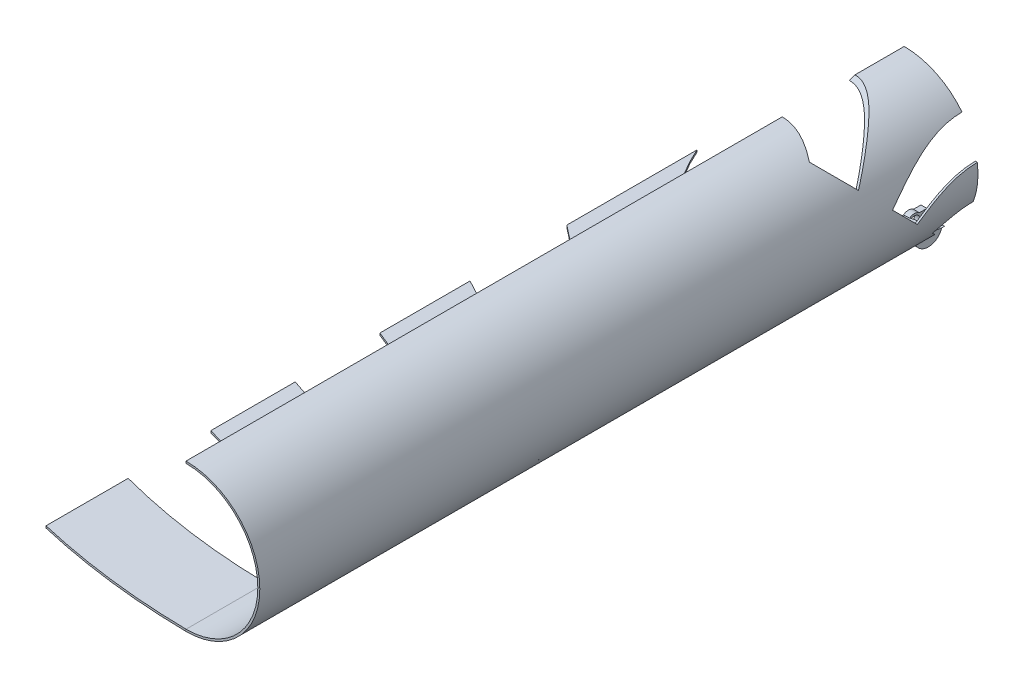
SolidWorks part; units mm, degrees
ref_plane "前视基准面" through (0, 0, 0) normal (0, 0, 1) x (1, 0, 0)
ref_plane "上视基准面" through (0, 0, 0) normal (0, 1, 0) x (1, 0, 0)
ref_plane "右视基准面" through (0, 0, 0) normal (1, 0, 0) x (0, 0, -1)
sketch "草图1" plane through (0, 0, 0) normal (0, 0, 1) x (1, 0, 0)
  circle A0 centre (0, 0) radius 18
  circle A1 centre (0, 0) radius 18.5
extrude "凸台-拉伸1" add sketch "草图1" along normal blind 180
sketch "草图2" plane through (0, 0, 0) normal (0, 0, -1) x (-1, 0, 0)
  line L0 (0, 0) -> (6.0887, 0)
  line L1 (0, 0) -> (0, 9.004)
sketch "草图3" plane through (0, 0, 180) normal (0, 0, 1) x (1, 0, 0)
  line L0 (0, 0) -> (-6.0887, 0)
  line L1 (0, 0) -> (0, 9.004)
ref_plane "基准面1" through (0, 0, 0) normal (1, 0, 0) x (0, 0, -1)
sketch "草图4" plane through (0, 0, 0) normal (1, 0, 0) x (0, 0, -1)
  line L0 (-2.1213, -16.3787) -> (-8.4853, -10.0147)
  line L1 (-23.7447, 23.2155) -> (0, 23.2155)
  line L2 (0, 23.2155) -> (0, 20.5)
  line L3 (0, -6.5) -> (0, -15.5)
  line L4 (-14.8492, -3.6508) -> (-21.2132, 2.7132)
  line L5 (0, 11.5) -> (0, 2.5)
  line L6 (-27.5772, 9.0772) -> (-33.9411, 15.4411)
  arc A0 (0, -15.5) -> (-2.1213, -16.3787) centre (0, -18.5) ccw
  arc A1 (0, -6.5) -> (-8.4853, -10.0147) centre (0, -18.5) ccw
  arc A2 (0, 2.5) -> (-14.8492, -3.6508) centre (0, -18.5) ccw
  arc A3 (0, 11.5) -> (-21.2132, 2.7132) centre (0, -18.5) ccw
  arc A4 (0, 20.5) -> (-27.5772, 9.0772) centre (0, -18.5) ccw
  arc A5 (-23.7447, 23.2155) -> (-33.9411, 15.4411) centre (0, -18.5) ccw
extrude "切除-拉伸1" cut sketch "草图4" against normal mid plane 60
ref_plane "基准面2" through (0, 0, 0) normal (0, 1, 0) x (1, 0, 0)
sketch "草图6" plane through (0, 0, 0) normal (0, 0, -1) x (-1, 0, 0)
  arc A0 (-10.0995, -15.5) -> (10.0995, -15.5) centre (0, 0) ccw construction
  point P0 (0, -18.5)
ref_point "点1"
ref_plane "基准面3" through (0, -18.5, 0) normal (0, 1, 0) x (1, 0, 0)
sketch "草图5" plane through (0, 0, 0) normal (1, 0, 0) x (0, 0, -1)
  line L2 (-0.1901, -18) -> (-2.0721, -18)
  line L3 (2.3114, -18) -> (4.1934, -18)
  arc A2 (-2.0721, -18) -> (4.1934, -18) centre (1.0607, -19.5607) ccw
  arc A5 (2.3114, -18) -> (-0.1901, -18) centre (1.0607, -19.5607) ccw
  circle A6 centre (1.0607, -19.5607) radius 1.5
  point P0 (0, -18)
extrude "凸台-拉伸2" add sketch "草图5" along normal mid plane 10
ref_plane "基准面4" through (3.5, 0, 0) normal (1, 0, 0) x (0, 0, -1)
sketch "草图8" plane through (3.5, 0, 0) normal (1, 0, 0) x (0, 0, -1)
  line L0 (-0.1901, -18) -> (-2.0721, -18)
  line L1 (2.3114, -18) -> (4.1934, -18)
  circle A0 centre (1.0607, -19.5607) radius 1.5
  arc A1 (2.3114, -18) -> (-0.1901, -18) centre (1.0607, -19.5607) ccw
  arc A2 (-2.0721, -18) -> (4.1934, -18) centre (1.0607, -19.5607) ccw
extrude "切除-拉伸2" cut sketch "草图8" against normal blind 2
ref_plane "基准面5" through (-1.5, 0, 0) normal (1, 0, 0) x (0, 0, -1)
sketch "草图9" plane through (-1.5, 0, 0) normal (1, 0, 0) x (0, 0, -1)
  line L0 (-2.0721, -18) -> (-0.1901, -18)
  line L1 (2.3114, -18) -> (4.1934, -18)
  circle A0 centre (1.0607, -19.5607) radius 1.5
  arc A1 (2.3114, -18) -> (-0.1901, -18) centre (1.0607, -19.5607) ccw
  arc A2 (-2.0721, -18) -> (4.1934, -18) centre (1.0607, -19.5607) ccw
extrude "切除-拉伸3" cut sketch "草图9" against normal blind 2
sketch "草图15" plane through (0, 0, 0) normal (0, 0, -1) x (-1, 0, 0)
  line L0 (0, 21.9854) -> (19.6473, 21.9854)
  line L1 (0, 21.9854) -> (0, -26.4376)
  line L2 (19.6473, 21.9854) -> (19.6473, -26.4376)
  line L3 (0, -26.4376) -> (19.6473, -26.4376)
  line L4 (0, 25.0366) -> (0, -25.0366) construction
extrude "切除-拉伸7" cut sketch "草图15" against normal mid plane 417
sketch "草图16" plane through (0, 0, 0) normal (1, 0, 0) x (0, 0, -1)
  line L0 (-80, -18.5) -> (-100, -18.5)
  line L1 (-180, -18.5) -> (-2.2748, -18.5) construction
  line L2 (-40, -18.5) -> (-60, -18.5)
  line L3 (-40, -18.5) -> (-40, -18)
  line L4 (-60, -18.5) -> (-60, -18)
  line L5 (-40, -18) -> (-60, -18)
  line L6 (-80, -18.5) -> (-80, -18)
  line L7 (-80, -18) -> (-100, -18)
  line L8 (-100, -18.5) -> (-100, -18)
  line L9 (-40, -18.5) -> (-80, -18.5) construction
  line L10 (-120, -18.5) -> (-140, -18.5)
  line L11 (-120, -18.5) -> (-120, -18)
  line L12 (-120, -18) -> (-140, -18)
  line L13 (-140, -18.5) -> (-140, -18)
  line L14 (-160, -18.5) -> (-180, -18.5)
  line L15 (-160, -18.5) -> (-160, -18)
  line L16 (-160, -18) -> (-180, -18)
  line L17 (-180, -18.5) -> (-180, -18)
  dimension "D1" = 4
  dimension "D2" = 20
  dimension "D3" = 0.5
  dimension "D4" = 40
extrude "凸台-拉伸4" add sketch "草图16" against normal blind 40
sketch "草图17" plane through (0, 0, 0) normal (1, 0, 0) x (0, 0, -1)
  line L0 (-100, -18.5) -> (-120, -18.5)
  line L1 (-140, -18.5) -> (-160, -18.5)
  line L6 (-60, -18.5) -> (-80, -18.5)
  line L7 (-60, -18.5) -> (-60, -17.5)
  line L8 (-80, -18.5) -> (-80, -17.5)
  line L9 (-60, -17.5) -> (-80, -17.5)
  line L10 (-80, -18.5) -> (-60, -18.5) construction
  line L11 (-100, -18.5) -> (-100, -17.5)
  line L12 (-100, -17.5) -> (-120, -17.5)
  line L13 (-120, -18.5) -> (-120, -17.5)
  line L14 (-60, -18.5) -> (-100, -18.5) construction
  line L15 (-140, -18.5) -> (-140, -17.5)
  line L16 (-140, -17.5) -> (-160, -17.5)
  line L17 (-160, -18.5) -> (-160, -17.5)
  dimension "D1" = 3
  dimension "D2" = 20
  dimension "D3" = 1
  dimension "D4" = 40
extrude "切除-拉伸8" cut sketch "草图17" along normal blind 40
sketch "草图20" plane through (0, -18.5, 0) normal (0, -1, 0) x (1, 0, 0)
  line L0 (0, 59.9528) -> (0, 39.9323)
  line L2 (-40, 68.8142) -> (-40, 91.1252)
  line L4 (-40, 11.916) -> (-40, 44.5562)
  line L6 (0, 180) -> (0, 159.99)
  line L7 (0, 99.9706) -> (0, 79.9808)
  line L8 (-40, 112.6284) -> (-40, 133.6863)
  line L9 (0, 139.9786) -> (0, 119.9752)
  line L10 (-40, 154.4833) -> (-40, 175.1021)
  arc A0 (0, 39.9323) -> (-40, 11.916) centre (2.5, -6.2) ccw
  arc A1 (0, 59.9528) -> (-40, 44.5562) centre (2.5, -6.2) ccw
  arc A2 (0, 79.9808) -> (-40, 68.8142) centre (2.5, -6.2) ccw
  arc A3 (0, 99.9706) -> (-40, 91.1252) centre (2.5, -6.2) ccw
  arc A4 (0, 119.9752) -> (-40, 112.6284) centre (2.5, -6.2) ccw
  arc A5 (0, 139.9786) -> (-40, 133.6863) centre (2.5, -6.2) ccw
  arc A6 (0, 159.99) -> (-40, 154.4833) centre (2.5, -6.2) ccw
  arc A7 (0, 180) -> (-40, 175.1021) centre (2.5, -6.2) ccw
extrude "凸台-拉伸8" add sketch "草图20" against normal blind 0.5
sketch "草图21" plane through (0, -18.5, 0) normal (0, -1, 0) x (1, 0, 0)
  line L0 (0, 79.9808) -> (0, 59.9528)
  line L1 (-40, 91.4051) -> (-40, 112.6284)
  line L3 (-40, 44.5562) -> (-40, 68.8142)
  line L5 (0, 159.99) -> (0, 140.0791)
  line L6 (0, 119.9752) -> (0, 100.2273)
  line L7 (-40, 133.7914) -> (-40, 154.4833)
  line L8 (-40, 175.0848) -> (-40, 180)
  line L9 (-40, 180) -> (-40, 184.5823)
  line L10 (-35.3294, 184.0453) -> (0, 179.9832)
  line L11 (-40, 184.5823) -> (-35.3294, 184.0453)
  arc A1 (0, 59.9528) -> (-40, 44.5562) centre (2.5, -6.2) ccw
  arc A2 (0, 79.9808) -> (-40, 68.8142) centre (2.5, -6.2) ccw
  arc A3 (0, 100.2273) -> (-40, 91.4051) centre (2.5, -6.2) ccw
  arc A4 (0, 119.9752) -> (-40, 112.6284) centre (2.5, -6.2) ccw
  arc A5 (0, 140.0791) -> (-40, 133.7914) centre (2.5, -6.2) ccw
  arc A6 (0, 159.99) -> (-40, 154.4833) centre (2.5, -6.2) ccw
  arc A7 (0, 179.9832) -> (-40, 175.0848) centre (2.5, -6.2) ccw
extrude "切除-拉伸10" cut sketch "草图21" against normal blind 0.5
ref_point "点2"
